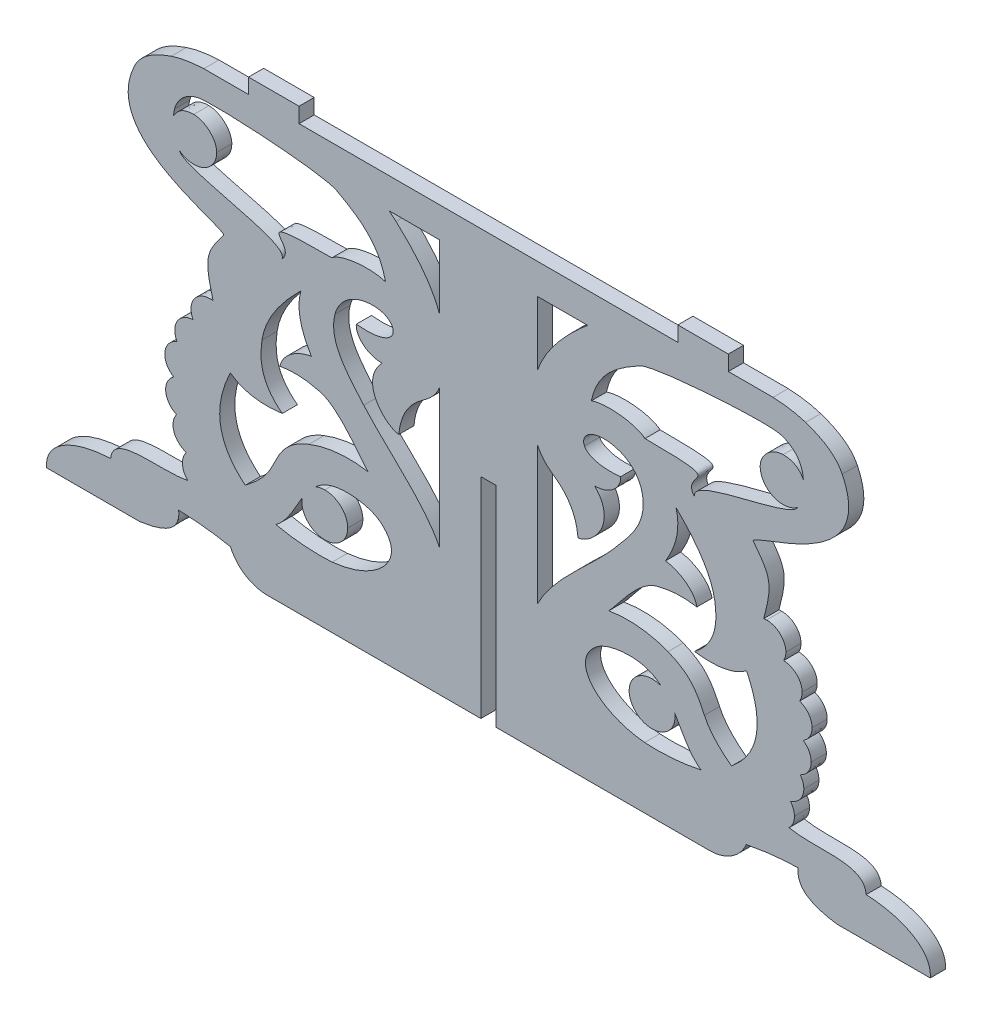
SolidWorks part; units mm, degrees
ref_plane "Plano frontal" through (0, 0, 0) normal (0, 0, 1) x (1, 0, 0)
ref_plane "Plano superior" through (0, 0, 0) normal (0, 1, 0) x (1, 0, 0)
ref_plane "Plano direito" through (0, 0, 0) normal (1, 0, 0) x (0, 0, -1)
sketch "Model" plane through (0, 0, 0) normal (0, 0, 1) x (1, 0, 0)
  line L29 (-58.0295, -132.7237) -> (-45.7155, -132.7237)
  line L30 (-28.8751, -132.7237) -> (-0.7099, -132.7237)
  line L31 (-0.7099, -132.7237) -> (-0.7099, -105.0626)
  line L32 (-0.7099, -105.0626) -> (1.2901, -105.0626)
  line L33 (1.2901, -105.0626) -> (1.2901, -132.7237)
  line L34 (1.2901, -132.7237) -> (29.4553, -132.7237)
  line L35 (46.2957, -132.7237) -> (58.6097, -132.7237)
  line L36 (37.859, -76.7198) -> (31.9567, -76.7198)
  line L37 (31.9567, -76.7198) -> (31.9567, -74.7247)
  line L38 (31.9567, -74.7247) -> (25.2901, -74.7247)
  line L39 (25.2901, -74.7247) -> (25.2901, -76.7198)
  line L40 (-24.7099, -76.7198) -> (-24.7099, -74.7247)
  line L41 (-24.7099, -74.7247) -> (-31.3766, -74.7247)
  line L42 (-31.3766, -74.7247) -> (-31.3766, -76.7198)
  line L43 (-31.3766, -76.7198) -> (-37.2789, -76.7198)
  line L44 (41.8464, -84.1013) -> (41.8509, -84.0772)
  line L45 (27.4601, -93.2254) -> (27.5114, -93.2255)
  line L46 (6.7678, -115.8622) -> (6.7678, -97.6611)
  line L47 (25.2636, -95.9326) -> (25.2605, -95.9344)
  line L48 (25.2605, -95.9344) -> (25.2233, -95.8931)
  line L49 (6.7678, -89.1619) -> (6.7678, -80.731)
  line L50 (6.7678, -80.731) -> (13.3925, -80.731)
  line L51 (-41.2663, -84.1013) -> (-41.2707, -84.0772)
  line L52 (-26.8799, -93.2254) -> (-26.9313, -93.2255)
  line L53 (-6.1877, -115.8622) -> (-6.1877, -97.6611)
  line L54 (-24.6834, -95.9326) -> (-24.6804, -95.9344)
  line L55 (-24.6804, -95.9344) -> (-24.6431, -95.8931)
  line L56 (-6.1877, -89.1619) -> (-6.1877, -80.731)
  line L57 (-6.1877, -80.731) -> (-12.8123, -80.731)
  spline S135 degree 3 poles (-37.2789, -76.7198) (-38.8553, -76.7842) (-40.3345, -77.0212) (-41.5726, -77.4345) knots 0 0 0 0 0.016393 0.016393 0.016393 0.016393
  spline S136 degree 3 poles (-41.5726, -77.4345) (-44.2957, -78.3435) (-45.7419, -79.5645) (-46.408, -80.9351) knots 0.016393 0.016393 0.016393 0.016393 0.032787 0.032787 0.032787 0.032787
  spline S137 degree 3 poles (-46.408, -80.9351) (-50.9976, -90.379) (-35.6947, -93.1676) (-34.6325, -94.4061) knots 0.032787 0.032787 0.032787 0.032787 0.04918 0.04918 0.04918 0.04918
  spline S138 degree 3 poles (-34.6325, -94.4061) (-36.8968, -97.3792) (-37.3095, -97.9852) (-36.0561, -102.6256) knots 0.04918 0.04918 0.04918 0.04918 0.065574 0.065574 0.065574 0.065574
  spline S139 degree 3 poles (-36.0561, -102.6256) (-36.178, -102.6086) (-36.3027, -102.5997) (-36.4296, -102.5997) knots 0.065574 0.065574 0.065574 0.065574 0.081967 0.081967 0.081967 0.081967
  spline S140 degree 3 poles (-36.4296, -102.5997) (-37.8337, -102.5997) (-38.9723, -103.6749) (-38.9723, -105.0007) knots 0.081967 0.081967 0.081967 0.081967 0.098361 0.098361 0.098361 0.098361
  spline S141 degree 3 poles (-38.9723, -105.0007) (-38.9723, -105.4037) (-38.8669, -105.7832) (-38.681, -106.1166) knots 0.098361 0.098361 0.098361 0.098361 0.114754 0.114754 0.114754 0.114754
  spline S142 degree 3 poles (-38.681, -106.1166) (-40.0347, -106.1704) (-41.1152, -107.2239) (-41.1152, -108.5154) knots 0.114754 0.114754 0.114754 0.114754 0.131148 0.131148 0.131148 0.131148
  spline S143 degree 3 poles (-41.1152, -108.5154) (-41.1152, -108.9387) (-40.9989, -109.3362) (-40.7951, -109.6816) knots 0.131148 0.131148 0.131148 0.131148 0.147541 0.147541 0.147541 0.147541
  spline S144 degree 3 poles (-40.7951, -109.6816) (-41.7518, -110.0264) (-42.4316, -110.9011) (-42.4316, -111.9255) knots 0.147541 0.147541 0.147541 0.147541 0.163934 0.163934 0.163934 0.163934
  spline S145 degree 3 poles (-42.4316, -111.9255) (-42.4316, -112.7766) (-41.9621, -113.524) (-41.2547, -113.9505) knots 0.163934 0.163934 0.163934 0.163934 0.180328 0.180328 0.180328 0.180328
  spline S146 degree 3 poles (-41.2547, -113.9505) (-41.8988, -114.3861) (-42.3188, -115.0988) (-42.3188, -115.9037) knots 0.180328 0.180328 0.180328 0.180328 0.196721 0.196721 0.196721 0.196721
  spline S147 degree 3 poles (-42.3188, -115.9037) (-42.3188, -116.8583) (-41.7284, -117.6825) (-40.874, -118.0695) knots 0.196721 0.196721 0.196721 0.196721 0.213115 0.213115 0.213115 0.213115
  spline S148 degree 3 poles (-40.874, -118.0695) (-41.1678, -118.4612) (-41.3407, -118.9396) (-41.3407, -119.456) knots 0.213115 0.213115 0.213115 0.213115 0.229508 0.229508 0.229508 0.229508
  spline S149 degree 3 poles (-41.3407, -119.456) (-41.3407, -120.5261) (-40.5988, -121.4327) (-39.5745, -121.7427) knots 0.229508 0.229508 0.229508 0.229508 0.245902 0.245902 0.245902 0.245902
  spline S150 degree 3 poles (-39.5745, -121.7427) (-39.9035, -122.1474) (-40.0993, -122.6538) (-40.0993, -123.2033) knots 0.245902 0.245902 0.245902 0.245902 0.262295 0.262295 0.262295 0.262295
  spline S151 degree 3 poles (-40.0993, -123.2033) (-40.0993, -123.846) (-39.8315, -124.4297) (-39.3959, -124.8607) knots 0.262295 0.262295 0.262295 0.262295 0.278689 0.278689 0.278689 0.278689
  spline S152 degree 3 poles (-39.3959, -124.8607) (-43.0969, -125.6187) (-49.2885, -124.0323) (-49.5679, -127.4221) knots 0.278689 0.278689 0.278689 0.278689 0.295082 0.295082 0.295082 0.295082
  spline S153 degree 3 poles (-49.5679, -127.4221) (-55.0145, -127.6994) (-58.2823, -129.8917) (-58.0295, -132.7237) knots 0.295082 0.295082 0.295082 0.295082 0.311475 0.311475 0.311475 0.311475
  spline S154 degree 3 poles (-45.7155, -132.7237) (-42.3585, -132.2526) (-40.3248, -131.1466) (-40.6026, -128.8422) knots 0.327869 0.327869 0.327869 0.327869 0.344262 0.344262 0.344262 0.344262
  spline S155 degree 3 poles (-40.6026, -128.8422) (-37.8869, -128.9335) (-35.6926, -129.2179) (-33.7519, -129.6077) knots 0.344262 0.344262 0.344262 0.344262 0.360656 0.360656 0.360656 0.360656
  spline S156 degree 3 poles (-33.7519, -129.6077) (-32.9718, -131.4296) (-31.0759, -132.7237) (-28.8751, -132.7237) knots 0.360656 0.360656 0.360656 0.360656 0.377049 0.377049 0.377049 0.377049
  spline S157 degree 3 poles (29.4553, -132.7237) (31.6561, -132.7237) (33.552, -131.4296) (34.3321, -129.6077) knots 0.459016 0.459016 0.459016 0.459016 0.47541 0.47541 0.47541 0.47541
  spline S158 degree 3 poles (34.3321, -129.6077) (36.2728, -129.2179) (38.4671, -128.9335) (41.1827, -128.8422) knots 0.47541 0.47541 0.47541 0.47541 0.491803 0.491803 0.491803 0.491803
  spline S159 degree 3 poles (41.1827, -128.8422) (40.905, -131.1466) (42.9386, -132.2526) (46.2957, -132.7237) knots 0.491803 0.491803 0.491803 0.491803 0.508197 0.508197 0.508197 0.508197
  spline S160 degree 3 poles (58.6097, -132.7237) (58.8625, -129.8917) (55.5947, -127.6994) (50.1481, -127.4221) knots 0.52459 0.52459 0.52459 0.52459 0.540984 0.540984 0.540984 0.540984
  spline S161 degree 3 poles (50.1481, -127.4221) (49.8687, -124.0323) (43.6771, -125.6187) (39.976, -124.8607) knots 0.540984 0.540984 0.540984 0.540984 0.557377 0.557377 0.557377 0.557377
  spline S162 degree 3 poles (39.976, -124.8607) (40.4117, -124.4297) (40.6794, -123.846) (40.6794, -123.2033) knots 0.557377 0.557377 0.557377 0.557377 0.57377 0.57377 0.57377 0.57377
  spline S163 degree 3 poles (40.6794, -123.2033) (40.6794, -122.6538) (40.4836, -122.1474) (40.1546, -121.7427) knots 0.57377 0.57377 0.57377 0.57377 0.590164 0.590164 0.590164 0.590164
  spline S164 degree 3 poles (40.1546, -121.7427) (41.1789, -121.4327) (41.9209, -120.5261) (41.9209, -119.456) knots 0.590164 0.590164 0.590164 0.590164 0.606557 0.606557 0.606557 0.606557
  spline S165 degree 3 poles (41.9209, -119.456) (41.9209, -118.9396) (41.748, -118.4612) (41.4541, -118.0695) knots 0.606557 0.606557 0.606557 0.606557 0.622951 0.622951 0.622951 0.622951
  spline S166 degree 3 poles (41.4541, -118.0695) (42.3085, -117.6825) (42.8989, -116.8583) (42.8989, -115.9037) knots 0.622951 0.622951 0.622951 0.622951 0.639344 0.639344 0.639344 0.639344
  spline S167 degree 3 poles (42.8989, -115.9037) (42.8989, -115.0988) (42.4789, -114.3861) (41.8349, -113.9505) knots 0.639344 0.639344 0.639344 0.639344 0.655738 0.655738 0.655738 0.655738
  spline S168 degree 3 poles (41.8349, -113.9505) (42.5423, -113.524) (43.0118, -112.7766) (43.0118, -111.9255) knots 0.655738 0.655738 0.655738 0.655738 0.672131 0.672131 0.672131 0.672131
  spline S169 degree 3 poles (43.0118, -111.9255) (43.0118, -110.9011) (42.3319, -110.0264) (41.3753, -109.6816) knots 0.672131 0.672131 0.672131 0.672131 0.688525 0.688525 0.688525 0.688525
  spline S170 degree 3 poles (41.3753, -109.6816) (41.5791, -109.3362) (41.6954, -108.9387) (41.6954, -108.5154) knots 0.688525 0.688525 0.688525 0.688525 0.704918 0.704918 0.704918 0.704918
  spline S171 degree 3 poles (41.6954, -108.5154) (41.6954, -107.2239) (40.6149, -106.1704) (39.2612, -106.1166) knots 0.704918 0.704918 0.704918 0.704918 0.721311 0.721311 0.721311 0.721311
  spline S172 degree 3 poles (39.2612, -106.1166) (39.447, -105.7832) (39.5524, -105.4037) (39.5524, -105.0007) knots 0.721311 0.721311 0.721311 0.721311 0.737705 0.737705 0.737705 0.737705
  spline S173 degree 3 poles (39.5524, -105.0007) (39.5524, -103.6749) (38.4138, -102.5997) (37.0097, -102.5997) knots 0.737705 0.737705 0.737705 0.737705 0.754098 0.754098 0.754098 0.754098
  spline S174 degree 3 poles (37.0097, -102.5997) (36.8829, -102.5997) (36.7582, -102.6086) (36.6363, -102.6256) knots 0.754098 0.754098 0.754098 0.754098 0.770492 0.770492 0.770492 0.770492
  spline S175 degree 3 poles (36.6363, -102.6256) (37.8897, -97.9852) (37.477, -97.3792) (35.2126, -94.4061) knots 0.770492 0.770492 0.770492 0.770492 0.786885 0.786885 0.786885 0.786885
  spline S176 degree 3 poles (35.2126, -94.4061) (36.2749, -93.1676) (51.5777, -90.379) (46.9881, -80.9351) knots 0.786885 0.786885 0.786885 0.786885 0.803279 0.803279 0.803279 0.803279
  spline S177 degree 3 poles (46.9881, -80.9351) (46.322, -79.5645) (44.8758, -78.3435) (42.1528, -77.4345) knots 0.803279 0.803279 0.803279 0.803279 0.819672 0.819672 0.819672 0.819672
  spline S178 degree 3 poles (42.1528, -77.4345) (40.9147, -77.0212) (39.4354, -76.7842) (37.859, -76.7198) knots 0.819672 0.819672 0.819672 0.819672 0.836066 0.836066 0.836066 0.836066
  spline S179 degree 3 poles (25.2901, -76.7198) (-24.0393, -76.7198) (24.6194, -76.7198) (-24.7099, -76.7198) knots 0.901639 0.901639 0.901639 0.901639 0.918033 0.918033 0.918033 0.918033
  spline S180 degree 3 poles (41.0991, -87.676) (40.5779, -88.0781) (39.9123, -88.3192) (39.1869, -88.3193) knots 0 0 0 0 0.071429 0.071429 0.071429 0.071429
  spline S181 degree 3 poles (39.1869, -88.3193) (37.5166, -88.3192) (36.162, -87.0406) (36.162, -85.4632) knots 0.071429 0.071429 0.071429 0.071429 0.142857 0.142857 0.142857 0.142857
  spline S182 degree 3 poles (36.162, -85.4632) (36.162, -83.8859) (37.7777, -82.6064) (39.1869, -82.6064) knots 0.142857 0.142857 0.142857 0.142857 0.214286 0.214286 0.214286 0.214286
  spline S183 degree 3 poles (39.1869, -82.6064) (40.5962, -82.6063) (41.3341, -83.211) (41.8464, -84.1013) knots 0.214286 0.214286 0.214286 0.214286 0.285714 0.285714 0.285714 0.285714
  spline S184 degree 3 poles (41.8509, -84.0772) (41.8313, -83.7922) (41.7887, -83.5147) (41.7202, -83.2484) knots 0.357143 0.357143 0.357143 0.357143 0.428571 0.428571 0.428571 0.428571
  spline S185 degree 3 poles (41.7202, -83.2484) (41.4272, -82.1106) (40.448, -80.7996) (38.5962, -80.4169) knots 0.428571 0.428571 0.428571 0.428571 0.5 0.5 0.5 0.5
  spline S186 degree 3 poles (38.5962, -80.4169) (36.406, -79.964) (22.1887, -80.8345) (20.2699, -81.9129) knots 0.5 0.5 0.5 0.5 0.571429 0.571429 0.571429 0.571429
  spline S187 degree 3 poles (20.2699, -81.9129) (17.8156, -83.2923) (14.7391, -84.986) (13.8733, -89.1082) knots 0.571429 0.571429 0.571429 0.571429 0.642857 0.642857 0.642857 0.642857
  spline S188 degree 3 poles (13.8733, -89.1082) (15.6554, -88.4485) (19.6405, -88.7534) (20.951, -89.8868) knots 0.642857 0.642857 0.642857 0.642857 0.714286 0.714286 0.714286 0.714286
  spline S189 degree 3 poles (20.951, -89.8868) (32.8615, -89.8868) (25.4889, -90.8661) (27.4601, -93.2254) knots 0.714286 0.714286 0.714286 0.714286 0.785714 0.785714 0.785714 0.785714
  spline S190 degree 3 poles (27.5114, -93.2255) (26.8882, -90.9726) (40.2299, -89.6032) (41.0991, -87.676) knots 0.857143 0.857143 0.857143 0.857143 1 1 1 1
  spline S191 degree 3 poles (6.7678, -97.6611) (7.1177, -98.522) (7.7821, -99.3416) (8.8217, -100.0587) knots 0.083333 0.083333 0.083333 0.083333 0.166667 0.166667 0.166667 0.166667
  spline S192 degree 3 poles (8.8217, -100.0587) (10.4062, -101.1516) (11.8709, -102.7858) (12.1135, -105.6647) knots 0.166667 0.166667 0.166667 0.166667 0.25 0.25 0.25 0.25
  spline S193 degree 3 poles (12.1135, -105.6647) (14.0789, -105.4211) (17.4305, -101.7668) (14.3074, -98.6123) knots 0.25 0.25 0.25 0.25 0.333333 0.333333 0.333333 0.333333
  spline S194 degree 3 poles (14.3074, -98.6123) (16.2667, -98.6614) (17.8601, -97.2088) (17.7312, -95.86) knots 0.333333 0.333333 0.333333 0.333333 0.416667 0.416667 0.416667 0.416667
  spline S195 degree 3 poles (17.7312, -95.86) (14.9058, -96.1563) (13.3648, -95.515) (12.9675, -94.7212) knots 0.416667 0.416667 0.416667 0.416667 0.5 0.5 0.5 0.5
  spline S196 degree 3 poles (12.9675, -94.7212) (12.7751, -94.3367) (12.8359, -93.9163) (13.1165, -93.5418) knots 0.5 0.5 0.5 0.5 0.583333 0.583333 0.583333 0.583333
  spline S197 degree 3 poles (13.1165, -93.5418) (13.9625, -92.4129) (16.199, -92.4035) (17.7583, -93.0431) knots 0.583333 0.583333 0.583333 0.583333 0.666667 0.666667 0.666667 0.666667
  spline S198 degree 3 poles (17.7583, -93.0431) (19.301, -93.6758) (20.2207, -94.8543) (20.5427, -96.1188) knots 0.666667 0.666667 0.666667 0.666667 0.75 0.75 0.75 0.75
  spline S199 degree 3 poles (20.5427, -96.1188) (21.4025, -99.4953) (19.0104, -102.0369) (16.7475, -104.6339) knots 0.75 0.75 0.75 0.75 0.833333 0.833333 0.833333 0.833333
  spline S200 degree 3 poles (16.7475, -104.6339) (13.6063, -108.239) (8.8067, -111.7552) (6.7678, -115.8622) knots 0.833333 0.833333 0.833333 0.833333 1 1 1 1
  spline S201 degree 3 poles (25.2233, -95.8931) (25.1662, -95.8373) (25.1087, -95.7815) (25.0509, -95.7255) knots 0.133333 0.133333 0.133333 0.133333 0.2 0.2 0.2 0.2
  spline S202 degree 3 poles (25.0509, -95.7255) (25.6852, -98.0721) (25.0055, -100.2976) (23.6733, -102.5024) knots 0.2 0.2 0.2 0.2 0.266667 0.266667 0.266667 0.266667
  spline S203 degree 3 poles (23.6733, -102.5024) (25.5011, -102.8033) (27.4577, -104.0051) (27.8065, -105.7119) knots 0.266667 0.266667 0.266667 0.266667 0.333333 0.333333 0.333333 0.333333
  spline S204 degree 3 poles (27.8065, -105.7119) (26.0758, -105.4045) (24.4417, -105.4953) (22.61, -105.9561) knots 0.333333 0.333333 0.333333 0.333333 0.4 0.4 0.4 0.4
  spline S205 degree 3 poles (22.61, -105.9561) (19.945, -106.6266) (17.4208, -110.716) (16.1735, -111.9637) knots 0.4 0.4 0.4 0.4 0.466667 0.466667 0.466667 0.466667
  spline S206 degree 3 poles (16.1735, -111.9637) (19.0564, -111.4458) (21.8473, -111.8747) (23.993, -112.7238) knots 0.466667 0.466667 0.466667 0.466667 0.533333 0.533333 0.533333 0.533333
  spline S207 degree 3 poles (23.993, -112.7238) (27.0207, -113.9218) (27.8131, -115.5233) (28.7997, -117.5912) knots 0.533333 0.533333 0.533333 0.533333 0.6 0.6 0.6 0.6
  spline S208 degree 3 poles (28.7997, -117.5912) (29.3141, -118.6694) (30.133, -119.916) (32.3886, -121.6047) knots 0.6 0.6 0.6 0.6 0.666667 0.666667 0.666667 0.666667
  spline S209 degree 3 poles (32.3886, -121.6047) (35.742, -118.8327) (36.9574, -115.1182) (34.3619, -109.7241) knots 0.666667 0.666667 0.666667 0.666667 0.733333 0.733333 0.733333 0.733333
  spline S210 degree 3 poles (34.3619, -109.7241) (32.6868, -111.0084) (30.2026, -111.343) (27.4986, -110.9533) knots 0.733333 0.733333 0.733333 0.733333 0.8 0.8 0.8 0.8
  spline S211 degree 3 poles (27.4986, -110.9533) (30.2732, -108.8598) (30.5616, -106.3477) (30.1795, -103.8887) knots 0.8 0.8 0.8 0.8 0.866667 0.866667 0.866667 0.866667
  spline S212 degree 3 poles (30.1795, -103.8887) (29.7867, -101.3608) (28.096, -98.7158) (25.2636, -95.9326) knots 0.866667 0.866667 0.866667 0.866667 1 1 1 1
  spline S213 degree 3 poles (21.8901, -116.8855) (20.2198, -116.8855) (18.8652, -118.1648) (18.8652, -119.7423) knots 0 0 0 0 0.090909 0.090909 0.090909 0.090909
  spline S214 degree 3 poles (18.8652, -119.7423) (18.8652, -121.3194) (20.2198, -122.5984) (21.8901, -122.5984) knots 0.090909 0.090909 0.090909 0.090909 0.181818 0.181818 0.181818 0.181818
  spline S215 degree 3 poles (21.8901, -122.5984) (23.5605, -122.5984) (24.915, -121.3194) (24.915, -119.7423) knots 0.181818 0.181818 0.181818 0.181818 0.272727 0.272727 0.272727 0.272727
  spline S216 degree 3 poles (24.915, -119.7423) (24.915, -119.5879) (24.9018, -119.4365) (24.8768, -119.2889) knots 0.272727 0.272727 0.272727 0.272727 0.363636 0.363636 0.363636 0.363636
  spline S217 degree 3 poles (24.8768, -119.2889) (25.9318, -120.9903) (26.7068, -122.8792) (28.3424, -124.0683) knots 0.363636 0.363636 0.363636 0.363636 0.454545 0.454545 0.454545 0.454545
  spline S218 degree 3 poles (28.3424, -124.0683) (25.7833, -124.6749) (22.5117, -124.8008) (20.911, -124.6529) knots 0.454545 0.454545 0.454545 0.454545 0.545455 0.545455 0.545455 0.545455
  spline S219 degree 3 poles (20.911, -124.6529) (15.1322, -124.1188) (10.6438, -119.9918) (14.5848, -116.8748) knots 0.545455 0.545455 0.545455 0.545455 0.636364 0.636364 0.636364 0.636364
  spline S220 degree 3 poles (14.5848, -116.8748) (16.0936, -115.6814) (19.8733, -115.2077) (22.0533, -116.3974) knots 0.636364 0.636364 0.636364 0.636364 0.727273 0.727273 0.727273 0.727273
  spline S221 degree 3 poles (22.0533, -116.3974) (22.4453, -116.6113) (22.7943, -116.8573) (23.1104, -117.1278) knots 0.727273 0.727273 0.727273 0.727273 0.818182 0.818182 0.818182 0.818182
  spline S222 degree 3 poles (23.1104, -117.1278) (22.7371, -116.972) (22.3244, -116.8855) (21.8901, -116.8855) knots 0.818182 0.818182 0.818182 0.818182 1 1 1 1
  spline S223 degree 3 poles (13.3925, -80.731) (13.0822, -80.9769) (12.7813, -81.2312) (12.4899, -81.4933) knots 0.4 0.4 0.4 0.4 0.6 0.6 0.6 0.6
  spline S224 degree 3 poles (12.4899, -81.4933) (9.9255, -83.8) (7.6953, -86.4622) (6.7678, -89.1619) knots 0.6 0.6 0.6 0.6 1 1 1 1
  spline S225 degree 3 poles (-40.5189, -87.676) (-39.9977, -88.0781) (-39.3321, -88.3192) (-38.6068, -88.3193) knots 0 0 0 0 0.071429 0.071429 0.071429 0.071429
  spline S226 degree 3 poles (-38.6068, -88.3193) (-36.9365, -88.3192) (-35.5819, -87.0406) (-35.5819, -85.4632) knots 0.071429 0.071429 0.071429 0.071429 0.142857 0.142857 0.142857 0.142857
  spline S227 degree 3 poles (-35.5819, -85.4632) (-35.5819, -83.8859) (-37.1975, -82.6064) (-38.6068, -82.6064) knots 0.142857 0.142857 0.142857 0.142857 0.214286 0.214286 0.214286 0.214286
  spline S228 degree 3 poles (-38.6068, -82.6064) (-40.016, -82.6063) (-40.754, -83.211) (-41.2663, -84.1013) knots 0.214286 0.214286 0.214286 0.214286 0.285714 0.285714 0.285714 0.285714
  spline S229 degree 3 poles (-41.2707, -84.0772) (-41.2511, -83.7922) (-41.2086, -83.5147) (-41.14, -83.2484) knots 0.357143 0.357143 0.357143 0.357143 0.428571 0.428571 0.428571 0.428571
  spline S230 degree 3 poles (-41.14, -83.2484) (-40.847, -82.1106) (-39.8679, -80.7996) (-38.0161, -80.4169) knots 0.428571 0.428571 0.428571 0.428571 0.5 0.5 0.5 0.5
  spline S231 degree 3 poles (-38.0161, -80.4169) (-35.8259, -79.964) (-21.6086, -80.8345) (-19.6898, -81.9129) knots 0.5 0.5 0.5 0.5 0.571429 0.571429 0.571429 0.571429
  spline S232 degree 3 poles (-19.6898, -81.9129) (-17.2355, -83.2923) (-14.1589, -84.986) (-13.2931, -89.1082) knots 0.571429 0.571429 0.571429 0.571429 0.642857 0.642857 0.642857 0.642857
  spline S233 degree 3 poles (-13.2931, -89.1082) (-15.0753, -88.4485) (-19.0603, -88.7534) (-20.3708, -89.8868) knots 0.642857 0.642857 0.642857 0.642857 0.714286 0.714286 0.714286 0.714286
  spline S234 degree 3 poles (-20.3708, -89.8868) (-32.2813, -89.8868) (-24.9088, -90.8661) (-26.8799, -93.2254) knots 0.714286 0.714286 0.714286 0.714286 0.785714 0.785714 0.785714 0.785714
  spline S235 degree 3 poles (-26.9313, -93.2255) (-26.308, -90.9726) (-39.6497, -89.6032) (-40.5189, -87.676) knots 0.857143 0.857143 0.857143 0.857143 1 1 1 1
  spline S236 degree 3 poles (-6.1877, -97.6611) (-6.5375, -98.522) (-7.202, -99.3416) (-8.2415, -100.0587) knots 0.083333 0.083333 0.083333 0.083333 0.166667 0.166667 0.166667 0.166667
  spline S237 degree 3 poles (-8.2415, -100.0587) (-9.826, -101.1516) (-11.2907, -102.7858) (-11.5334, -105.6647) knots 0.166667 0.166667 0.166667 0.166667 0.25 0.25 0.25 0.25
  spline S238 degree 3 poles (-11.5334, -105.6647) (-13.4988, -105.4211) (-16.8504, -101.7668) (-13.7272, -98.6123) knots 0.25 0.25 0.25 0.25 0.333333 0.333333 0.333333 0.333333
  spline S239 degree 3 poles (-13.7272, -98.6123) (-15.6865, -98.6614) (-17.2799, -97.2088) (-17.151, -95.86) knots 0.333333 0.333333 0.333333 0.333333 0.416667 0.416667 0.416667 0.416667
  spline S240 degree 3 poles (-17.151, -95.86) (-14.3257, -96.1563) (-12.7846, -95.515) (-12.3874, -94.7212) knots 0.416667 0.416667 0.416667 0.416667 0.5 0.5 0.5 0.5
  spline S241 degree 3 poles (-12.3874, -94.7212) (-12.195, -94.3367) (-12.2557, -93.9163) (-12.5364, -93.5418) knots 0.5 0.5 0.5 0.5 0.583333 0.583333 0.583333 0.583333
  spline S242 degree 3 poles (-12.5364, -93.5418) (-13.3823, -92.4129) (-15.6188, -92.4035) (-17.1782, -93.0431) knots 0.583333 0.583333 0.583333 0.583333 0.666667 0.666667 0.666667 0.666667
  spline S243 degree 3 poles (-17.1782, -93.0431) (-18.7209, -93.6758) (-19.6406, -94.8543) (-19.9625, -96.1188) knots 0.666667 0.666667 0.666667 0.666667 0.75 0.75 0.75 0.75
  spline S244 degree 3 poles (-19.9625, -96.1188) (-20.8224, -99.4953) (-18.4302, -102.0369) (-16.1674, -104.6339) knots 0.75 0.75 0.75 0.75 0.833333 0.833333 0.833333 0.833333
  spline S245 degree 3 poles (-16.1674, -104.6339) (-13.0261, -108.239) (-8.2265, -111.7552) (-6.1877, -115.8622) knots 0.833333 0.833333 0.833333 0.833333 1 1 1 1
  spline S246 degree 3 poles (-24.6431, -95.8931) (-24.5861, -95.8373) (-24.5286, -95.7815) (-24.4707, -95.7255) knots 0.133333 0.133333 0.133333 0.133333 0.2 0.2 0.2 0.2
  spline S247 degree 3 poles (-24.4707, -95.7255) (-25.105, -98.0721) (-24.4253, -100.2976) (-23.0931, -102.5024) knots 0.2 0.2 0.2 0.2 0.266667 0.266667 0.266667 0.266667
  spline S248 degree 3 poles (-23.0931, -102.5024) (-24.921, -102.8033) (-26.8776, -104.0051) (-27.2264, -105.7119) knots 0.266667 0.266667 0.266667 0.266667 0.333333 0.333333 0.333333 0.333333
  spline S249 degree 3 poles (-27.2264, -105.7119) (-25.4957, -105.4045) (-23.8615, -105.4953) (-22.0299, -105.9561) knots 0.333333 0.333333 0.333333 0.333333 0.4 0.4 0.4 0.4
  spline S250 degree 3 poles (-22.0299, -105.9561) (-19.3648, -106.6266) (-16.8406, -110.716) (-15.5933, -111.9637) knots 0.4 0.4 0.4 0.4 0.466667 0.466667 0.466667 0.466667
  spline S251 degree 3 poles (-15.5933, -111.9637) (-18.4762, -111.4458) (-21.2671, -111.8747) (-23.4129, -112.7238) knots 0.466667 0.466667 0.466667 0.466667 0.533333 0.533333 0.533333 0.533333
  spline S252 degree 3 poles (-23.4129, -112.7238) (-26.4406, -113.9218) (-27.233, -115.5233) (-28.2196, -117.5912) knots 0.533333 0.533333 0.533333 0.533333 0.6 0.6 0.6 0.6
  spline S253 degree 3 poles (-28.2196, -117.5912) (-28.734, -118.6694) (-29.5528, -119.916) (-31.8084, -121.6047) knots 0.6 0.6 0.6 0.6 0.666667 0.666667 0.666667 0.666667
  spline S254 degree 3 poles (-31.8084, -121.6047) (-35.1618, -118.8327) (-36.3773, -115.1182) (-33.7818, -109.7241) knots 0.666667 0.666667 0.666667 0.666667 0.733333 0.733333 0.733333 0.733333
  spline S255 degree 3 poles (-33.7818, -109.7241) (-32.1066, -111.0084) (-29.6224, -111.343) (-26.9184, -110.9533) knots 0.733333 0.733333 0.733333 0.733333 0.8 0.8 0.8 0.8
  spline S256 degree 3 poles (-26.9184, -110.9533) (-29.693, -108.8598) (-29.9814, -106.3477) (-29.5994, -103.8887) knots 0.8 0.8 0.8 0.8 0.866667 0.866667 0.866667 0.866667
  spline S257 degree 3 poles (-29.5994, -103.8887) (-29.2066, -101.3608) (-27.5159, -98.7158) (-24.6834, -95.9326) knots 0.866667 0.866667 0.866667 0.866667 1 1 1 1
  spline S258 degree 3 poles (-21.3099, -116.8855) (-19.6397, -116.8855) (-18.2851, -118.1648) (-18.2851, -119.7423) knots 0 0 0 0 0.090909 0.090909 0.090909 0.090909
  spline S259 degree 3 poles (-18.2851, -119.7423) (-18.2851, -121.3194) (-19.6397, -122.5984) (-21.3099, -122.5984) knots 0.090909 0.090909 0.090909 0.090909 0.181818 0.181818 0.181818 0.181818
  spline S260 degree 3 poles (-21.3099, -122.5984) (-22.9803, -122.5984) (-24.3349, -121.3194) (-24.3349, -119.7423) knots 0.181818 0.181818 0.181818 0.181818 0.272727 0.272727 0.272727 0.272727
  spline S261 degree 3 poles (-24.3349, -119.7423) (-24.3349, -119.5879) (-24.3216, -119.4365) (-24.2967, -119.2889) knots 0.272727 0.272727 0.272727 0.272727 0.363636 0.363636 0.363636 0.363636
  spline S262 degree 3 poles (-24.2967, -119.2889) (-25.3516, -120.9903) (-26.1266, -122.8792) (-27.7623, -124.0683) knots 0.363636 0.363636 0.363636 0.363636 0.454545 0.454545 0.454545 0.454545
  spline S263 degree 3 poles (-27.7623, -124.0683) (-25.2031, -124.6749) (-21.9316, -124.8008) (-20.3309, -124.6529) knots 0.454545 0.454545 0.454545 0.454545 0.545455 0.545455 0.545455 0.545455
  spline S264 degree 3 poles (-20.3309, -124.6529) (-14.552, -124.1188) (-10.0636, -119.9918) (-14.0046, -116.8748) knots 0.545455 0.545455 0.545455 0.545455 0.636364 0.636364 0.636364 0.636364
  spline S265 degree 3 poles (-14.0046, -116.8748) (-15.5134, -115.6814) (-19.2931, -115.2077) (-21.4731, -116.3974) knots 0.636364 0.636364 0.636364 0.636364 0.727273 0.727273 0.727273 0.727273
  spline S266 degree 3 poles (-21.4731, -116.3974) (-21.8651, -116.6113) (-22.2141, -116.8573) (-22.5303, -117.1278) knots 0.727273 0.727273 0.727273 0.727273 0.818182 0.818182 0.818182 0.818182
  spline S267 degree 3 poles (-22.5303, -117.1278) (-22.157, -116.972) (-21.7442, -116.8855) (-21.3099, -116.8855) knots 0.818182 0.818182 0.818182 0.818182 1 1 1 1
  spline S268 degree 3 poles (-12.8123, -80.731) (-12.5021, -80.9769) (-12.2011, -81.2312) (-11.9097, -81.4933) knots 0.4 0.4 0.4 0.4 0.6 0.6 0.6 0.6
  spline S269 degree 3 poles (-11.9097, -81.4933) (-9.3454, -83.8) (-7.1151, -86.4622) (-6.1877, -89.1619) knots 0.6 0.6 0.6 0.6 1 1 1 1
extrude "Ressalto-extrusão1" add sketch "Model" along normal blind 2
